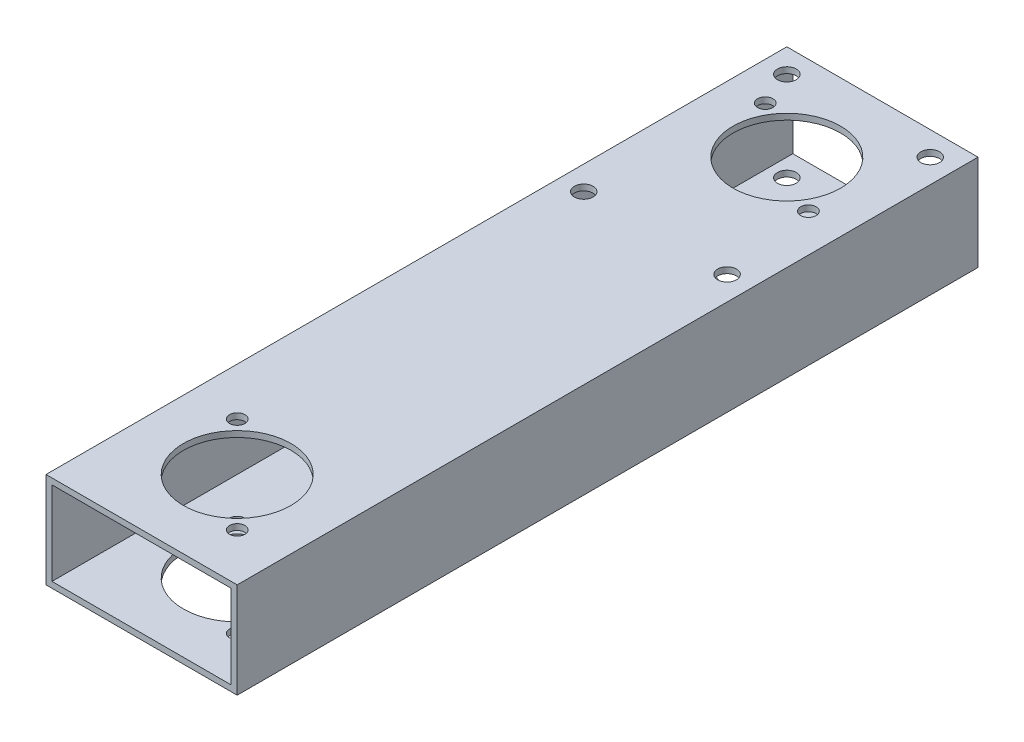
SolidWorks part; units mm, degrees
material "6061 Alloy"
ref_plane "Front Plane" through (0, 0, 0) normal (0, 0, 1) x (1, 0, 0)
ref_plane "Top Plane" through (0, 0, 0) normal (0, 1, 0) x (1, 0, 0)
ref_plane "Right Plane" through (0, 0, 0) normal (1, 0, 0) x (0, 0, -1)
sketch "Sketch1" plane through (0, 0, 0) normal (0, 0, 1) x (1, 0, 0)
  line L0 (-23.8125, 11.1125) -> (23.8125, 11.1125)
  line L2 (-25.4, 12.7) -> (25.4, 12.7)
  line L3 (-25.4, 12.7) -> (-25.4, -12.7)
  line L4 (-25.4, -12.7) -> (25.4, -12.7)
  line L5 (25.4, 12.7) -> (25.4, -12.7)
  line L10 (23.8125, 11.1125) -> (23.8125, -11.1125)
  line L11 (-23.8125, -11.1125) -> (23.8125, -11.1125)
  line L12 (-23.8125, 11.1125) -> (-23.8125, -11.1125)
  point P12 (0, 12.7)
  point P14 (25.4, 0)
  dimension "Wall Thickness" = 1.5875
  dimension "Outside Width" = 50.8
  dimension "Outside Height" = 25.4
  dimension "Inside Height" = 22.225
  dimension "Inside Width" = 47.625
sketch "Sketch2" plane through (0, 0, 0) normal (1, 0, 0) x (0, 0, -1)
  line L0 (98.425, 0) -> (-98.425, 0)
  point P4 (0, 0)
  point P7 (-98.425, 0)
  point P10 (98.425, 0)
  dimension "Length" = 196.85
sketch "Sketch3" plane through (0, 0, 0) normal (0, 0, 1) x (1, 0, 0)
  line L21 (25.4, 12.7) -> (-25.4, 12.7)
  line L22 (25.4, -12.7) -> (25.4, 12.7)
  line L23 (-25.4, -12.7) -> (25.4, -12.7)
  line L24 (-25.4, 12.7) -> (-25.4, -12.7)
  line L25 (25.4, 12.7) -> (-25.4, 12.7)
  line L26 (25.4, -12.7) -> (25.4, 12.7)
  line L27 (-25.4, -12.7) -> (25.4, -12.7)
  line L28 (-25.4, 12.7) -> (-25.4, -12.7)
  line L29 (23.8125, 11.1125) -> (-23.8125, 11.1125)
  line L30 (23.8125, -11.1125) -> (23.8125, 11.1125)
  line L31 (-23.8125, -11.1125) -> (23.8125, -11.1125)
  line L32 (-23.8125, 11.1125) -> (-23.8125, -11.1125)
  line L33 (23.8125, 11.1125) -> (-23.8125, 11.1125)
  line L34 (23.8125, -11.1125) -> (23.8125, 11.1125)
  line L35 (-23.8125, -11.1125) -> (23.8125, -11.1125)
  line L36 (-23.8125, 11.1125) -> (-23.8125, -11.1125)
  dimension "D1" = 0
  dimension "D2" = 0
extrude "Boss-Extrude1" add sketch "Sketch3" along normal up to vertex (98.425 mm away) and the other way up to vertex (98.425 mm away) up to point (0, 0, 98.425) other way up to point (0, 0, -98.425)
sketch "Drawing Reference" plane through (0, 0, 0) normal (1, 0, 0) x (0, 0, -1)
  line L0 (-98.425, 0) -> (98.425, 0) construction
  line L1 (0, -12.7) -> (0, 12.7) construction
  line L2 (-98.425, -12.7) -> (98.425, -12.7) construction
  line L5 (-98.425, 12.7) -> (98.425, 12.7) construction
  point P7 (-61.849, 0)
  point P8 (61.849, 0)
  dimension "D1" = 36.576
sketch "Sketch4" plane through (0, -12.7, 0) normal (0, -1, 0) x (1, 0, 0)
  line L0 (-25.4, 0) -> (0, 0) construction
  line L1 (-25.4, 98.425) -> (-25.4, -98.425) construction
  line L2 (0, 0) -> (0, -73.025) construction
  line L3 (0, 0) -> (0, 73.025) construction
  circle A0 centre (0, 73.025) radius 14.2875
  circle A1 centre (0, -73.025) radius 14.2875
extrude "Cut-Extrude3" cut sketch "Sketch4" against normal through all
hole_wizard "#10 Clearance Hole1" positions "Sketch5" profile "Sketch6" hole size "#10" standard "ANSI Inch" end condition through all
sketch "Sketch5" plane through (0, 12.7, 0) normal (0, 1, 0) x (1, 0, 0)
  point P0 (19.05, 38.1)
  point P3 (19.05, 92.075)
  point P6 (-19.05, 92.075)
  point P9 (-19.05, 38.1)
sketch "Sketch6" plane through (19.05, 12.7, -38.1) normal (1, 0, 0) x (0, 0, 1)
  line L0 (0, 0) -> (0, 25.4)
  line L1 (0, 25.4) -> (2.4892, 25.4)
  line L2 (2.4892, 25.4) -> (2.4892, 0)
  line L5 (2.4892, 0) -> (0, 0)
  line L11 (0, -6.35) -> (0, 107.95) construction
  dimension "Thru Hole Dia." = 4.9784
  dimension "Thru Hole Depth" = 25.4
sketch "Sketch7" plane through (0, -12.7, 0) normal (0, -1, 0) x (1, 0, 0)
  line L0 (-25.4, -31.75) -> (-342.9, -31.75) construction
  line L1 (-25.4, -31.75) -> (25.4, -31.75)
  line L2 (-25.4, 98.425) -> (-25.4, -98.425) construction
  line L3 (25.4, 98.425) -> (25.4, -98.425) construction
  line L4 (25.4, -31.75) -> (25.4, -98.425)
  line L5 (25.4, -98.425) -> (-25.4, -98.425)
  line L6 (-25.4, -98.425) -> (-25.4, -82.55)
  line L7 (-25.4, -82.55) -> (-342.9, -82.55) construction
  line L8 (-25.4, -82.55) -> (-104.2832, -82.55)
  line L9 (-104.2832, -82.55) -> (-104.2832, -31.75)
  line L10 (-104.2832, -31.75) -> (-25.4, -31.75)
  circle A0 centre (0, -73.2777) radius 14.5402
hole_wizard "#20 (0.161) Diameter Hole1" positions "Sketch8" profile "Sketch9" hole size "#20" standard "ANSI Inch" end condition through all
sketch "Sketch8" plane through (0, 12.7, 0) normal (0, 1, 0) x (1, 0, 0)
  point P0 (-12.752, -60.273)
  point P3 (12.752, -85.777)
sketch "Sketch9" plane through (-12.752, 12.7, 60.273) normal (1, 0, 0) x (0, 0, 1)
  line L0 (0, 0) -> (0, 25.4)
  line L1 (0, 25.4) -> (2.0447, 25.4)
  line L2 (2.0447, 25.4) -> (2.0447, 0)
  line L5 (2.0447, 0) -> (0, 0)
  line L11 (0, -6.35) -> (0, 107.95) construction
  dimension "Thru Hole Dia." = 4.0894
  dimension "Thru Hole Depth" = 25.4
hole_wizard "#20 (0.161) Diameter Hole2" positions "Sketch10" profile "Sketch11" hole size "#20" standard "ANSI Inch" end condition through all
sketch "Sketch10" plane through (0, 12.7, 0) normal (0, 1, 0) x (1, 0, 0)
  point P0 (-15.2937, 82.5816)
  point P3 (15.2937, 63.4684)
sketch "Sketch11" plane through (-15.2937, 12.7, -82.5816) normal (1, 0, 0) x (0, 0, 1)
  line L0 (0, 0) -> (0, 25.4)
  line L1 (0, 25.4) -> (2.0447, 25.4)
  line L2 (2.0447, 25.4) -> (2.0447, 0)
  line L5 (2.0447, 0) -> (0, 0)
  line L11 (0, -6.35) -> (0, 107.95) construction
  dimension "Thru Hole Dia." = 4.0894
  dimension "Thru Hole Depth" = 25.4
equation "\"D1@Drawing Reference\"=\"Outside Width@Sketch1\" * 0.72"
